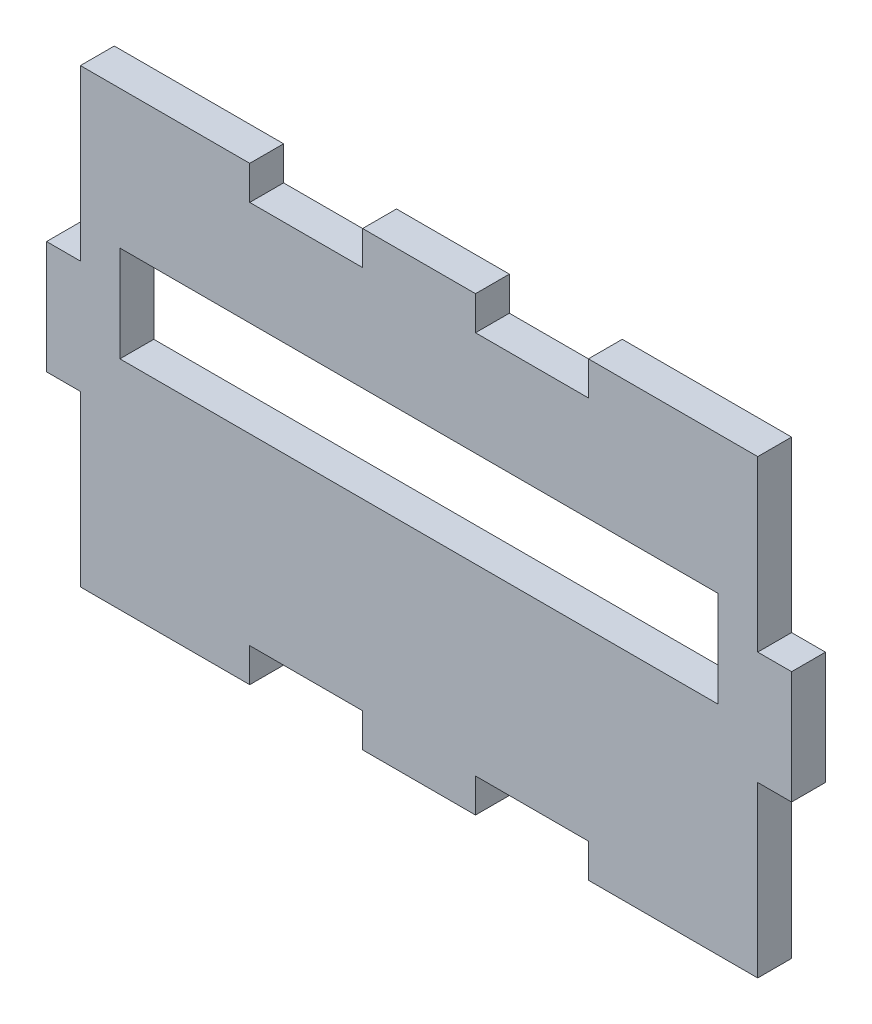
SolidWorks part; units mm, degrees
ref_plane "Plano frontal" through (0, 0, 0) normal (0, 0, 1) x (1, 0, 0)
ref_plane "Plano superior" through (0, 0, 0) normal (0, 1, 0) x (1, 0, 0)
ref_plane "Plano direito" through (0, 0, 0) normal (1, 0, 0) x (0, 0, -1)
sketch "Esboço1" plane through (0, 0, 0) normal (0, 0, 1) x (1, 0, 0)
  line L0 (-90, 0) -> (-90, 6)
  line L2 (0, 0) -> (0, 30)
  line L3 (0, 80) -> (-30, 80)
  line L4 (-120, 0) -> (-120, 30)
  line L5 (-90, 6) -> (-70, 6)
  line L6 (-70, 6) -> (-70, 0)
  line L7 (-120, 50) -> (-126, 50)
  line L8 (-126, 50) -> (-126, 30)
  line L9 (-126, 30) -> (-120, 30)
  line L10 (-90, 80) -> (-90, 74)
  line L11 (-90, 74) -> (-70, 74)
  line L12 (-70, 74) -> (-70, 80)
  line L13 (-50, 80) -> (-50, 74)
  line L14 (-50, 74) -> (-30, 74)
  line L15 (-30, 74) -> (-30, 80)
  line L16 (-50.0001, 0) -> (-50.0001, 6)
  line L17 (-50.0001, 6) -> (-30.0001, 6)
  line L18 (-30.0001, 6) -> (-30.0001, 0)
  line L19 (-120, 50) -> (-120, 80)
  line L20 (-90, 80) -> (-120, 80)
  line L22 (-50.0001, 0) -> (-70, 0)
  line L23 (-90, 0) -> (-120, 0)
  line L24 (0, 50) -> (6, 50)
  line L25 (6, 50) -> (6, 30)
  line L26 (6, 30) -> (0, 30)
  line L27 (0, 50) -> (0, 80)
  line L28 (-50, 80) -> (-70, 80)
  line L29 (-113, 38.5) -> (-7, 38.5)
  line L30 (-113, 38.5) -> (-113, 55.5)
  line L31 (-113, 55.5) -> (-7, 55.5)
  line L32 (-7, 38.5) -> (-7, 55.5)
  line L33 (0, 0) -> (-30.0001, 0)
  point P34 (-113, 47)
  point P35 (-126, 40)
  dimension "D1" = 80
  dimension "D2" = 120
  dimension "D3" = 6
  dimension "D4" = 6
  dimension "D5" = 20
  dimension "D6" = 20
  dimension "D7" = 17
  dimension "D8" = 7
  dimension "D9" = 30
  dimension "D10" = 20
  dimension "D11" = 6
  dimension "D12" = 20
  dimension "D13" = 19.9999
  dimension "D14" = 20
  dimension "D15" = 6
  dimension "D16" = 106
  dimension "D18" = 13
extrude "Ressalto-extrusão6" add sketch "Esboço1" along normal blind 6
